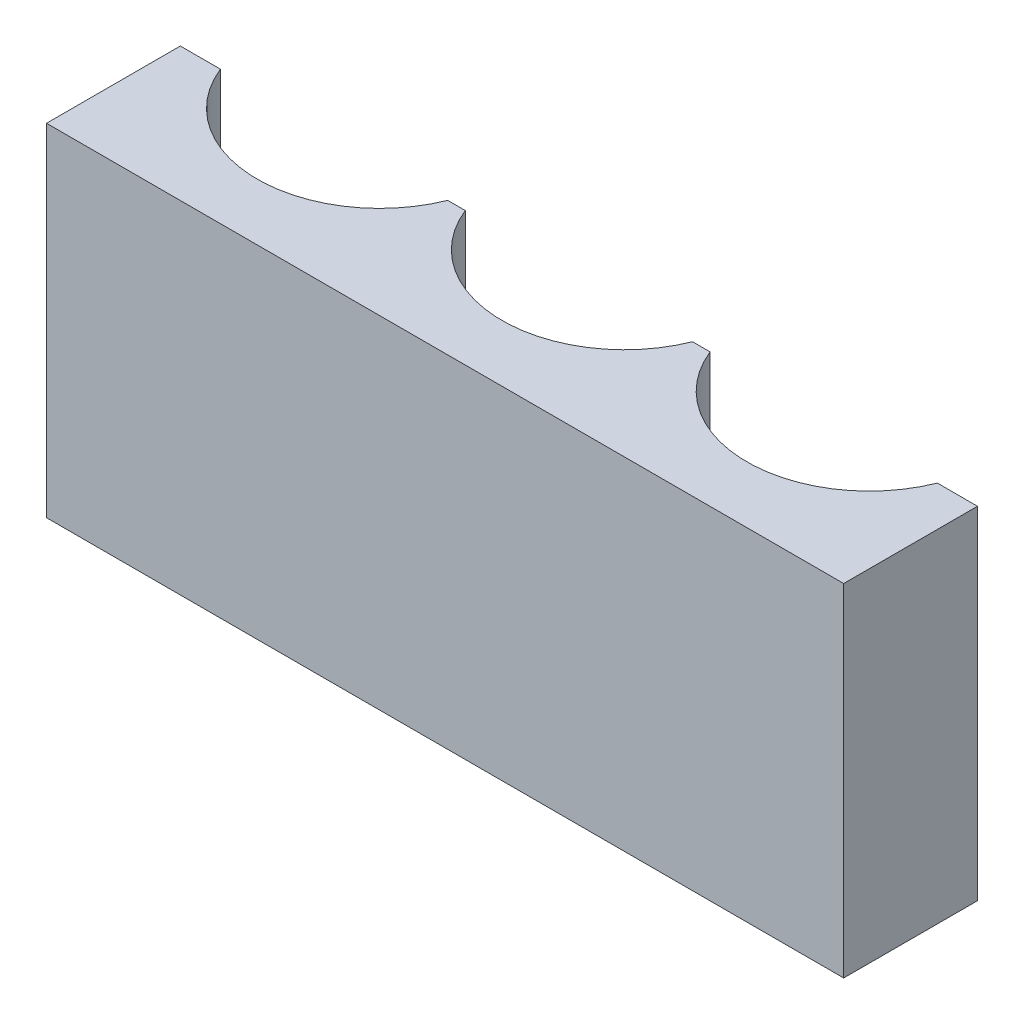
SolidWorks part; units mm, degrees
ref_plane "前视基准面" through (0, 0, 0) normal (0, 0, 1) x (1, 0, 0)
ref_plane "上视基准面" through (0, 0, 0) normal (0, 1, 0) x (1, 0, 0)
ref_plane "右视基准面" through (0, 0, 0) normal (1, 0, 0) x (0, 0, -1)
other "Configuration Table"
sketch "草图1" plane through (0, 0, 0) normal (0, 0, 1) x (1, 0, 0)
  line L1 (-35, 15) -> (35, 15)
  line L2 (-35, 15) -> (-35, -15)
  line L3 (-35, -15) -> (35, -15)
  line L4 (35, 15) -> (35, -15)
  line L5 (0, -15) -> (0, 15) construction
  line L6 (-35, 0) -> (35, 0) construction
  point P0 (0, 0)
  dimension "D1" = 30
  dimension "D2" = 70
extrude "凸台-拉伸1" add sketch "草图1" along normal blind 15.75
sketch "草图3" plane through (0, 15, 0) normal (0, 1, 0) x (1, 0, 0)
  line L0 (35, 0) -> (-35, 0) construction
  line L1 (-10.75, 0) -> (10.75, 0)
  line L2 (-32.25, 0) -> (-10.75, 0)
  line L3 (10.75, 0) -> (32.25, 0)
  arc A0 (10.75, 0) -> (-10.75, 0) centre (0, 0) cw
  arc A1 (-10.75, 0) -> (-32.25, 0) centre (-21.5, 0) cw
  arc A2 (32.25, 0) -> (10.75, 0) centre (21.5, 0) cw
  line M3 (35, 0) -> (-35, 0)
  dimension "D1" = 10.75
  dimension "D2" = 2
  dimension "D3" = 2
extrude "切除-拉伸1" cut sketch "草图3" against normal blind 30 contours A1 M3 | A0 M3 | A2 M3
sketch "草图4" plane through (0, 15, 0) normal (0, 1, 0) x (1, 0, 0)
  line L0 (35, -15.75) -> (35, 0) construction
  line L1 (-35, 0) -> (35, 0)
  line L2 (-35, 0) -> (-35, -4)
  line L3 (-35, -4) -> (35, -4)
  line L4 (35, 0) -> (35, -4)
  dimension "D1" = 4
extrude "切除-拉伸2" cut sketch "草图4" against normal blind 30
sketch "草图6" plane through (0, 0, 4) normal (0, 0, -1) x (-1, 0, 0)
  line L0 (19, 5) -> (19, -5)
  line L5 (-2.5, 5) -> (2.5, 5)
  line L6 (-2.5, 5) -> (-2.5, -5)
  line L7 (-2.5, -5) -> (2.5, -5)
  line L8 (2.5, 5) -> (2.5, -5)
  line L9 (0, -5) -> (0, 5) construction
  line L10 (-2.5, 0) -> (2.5, 0) construction
  line L11 (19, 5) -> (24, 5)
  line L12 (24, 5) -> (24, -5)
  line L13 (19, -5) -> (24, -5)
  line L14 (-24, 5) -> (-24, -5)
  line L15 (-24, 5) -> (-19, 5)
  line L16 (-19, 5) -> (-19, -5)
  line L17 (-24, -5) -> (-19, -5)
  point P4 (0, 0)
  dimension "D1" = 5
  dimension "D2" = 10
  dimension "D3" = 2
  dimension "D4" = 2
extrude "切除-拉伸3" cut sketch "草图6" against normal blind 10
